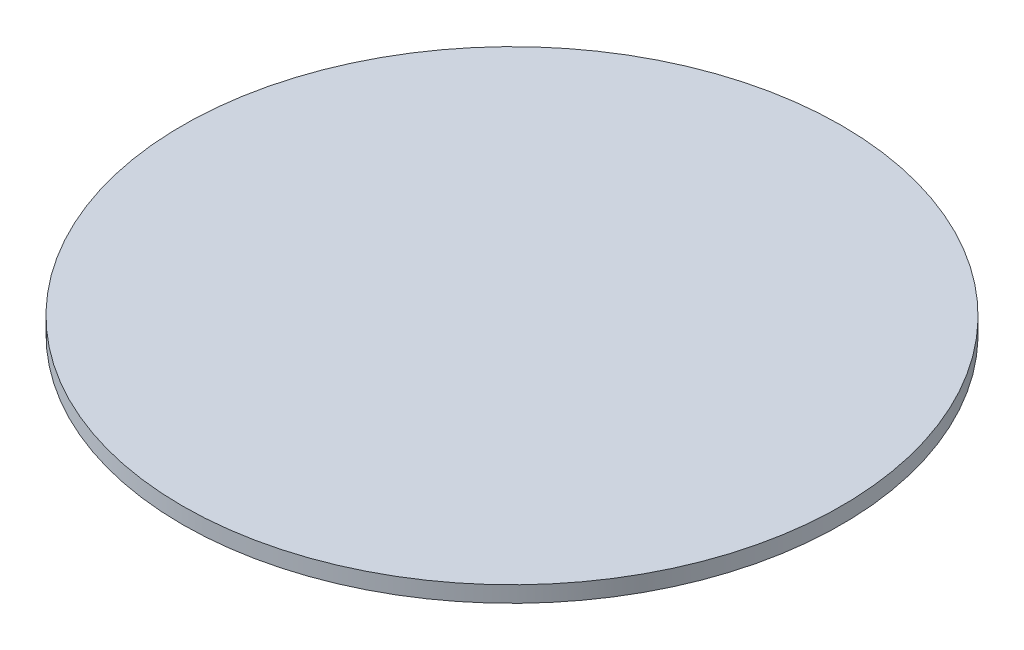
SolidWorks part; units mm, degrees
ref_plane "Front Plane" through (0, 0, 0) normal (0, 0, 1) x (1, 0, 0)
ref_plane "Top Plane" through (0, 0, 0) normal (0, 1, 0) x (1, 0, 0)
ref_plane "Right Plane" through (0, 0, 0) normal (1, 0, 0) x (0, 0, -1)
sketch "Sketch1" plane through (0, 0, 0) normal (0, 1, 0) x (1, 0, 0)
  circle A0 centre (0, 0) radius 102.5
  dimension "D1" = 205
extrude "Boss-Extrude1" add sketch "Sketch1" along normal blind 5
